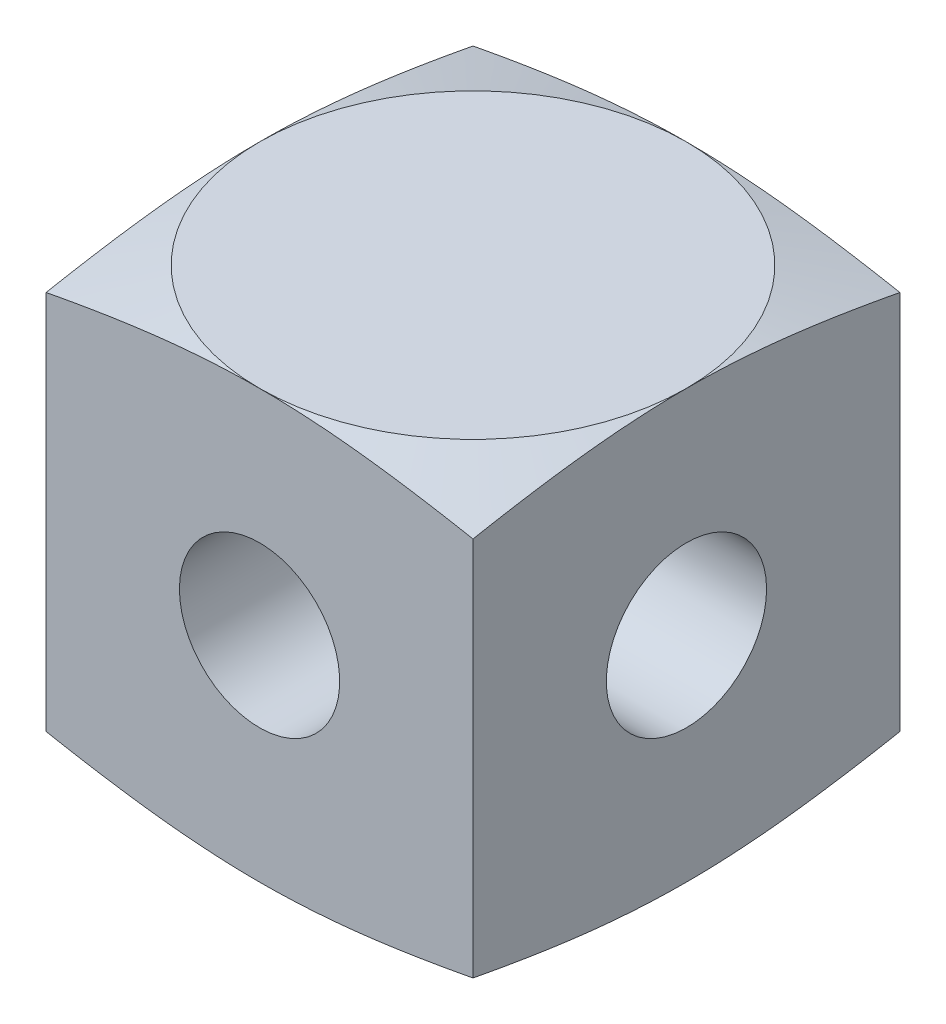
SolidWorks part; units mm, degrees
material "Plain Carbon Steel"
ref_plane "Front Plane" through (0, 0, 0) normal (0, 0, 1) x (1, 0, 0)
ref_plane "Top Plane" through (0, 0, 0) normal (0, 1, 0) x (1, 0, 0)
ref_plane "Right Plane" through (0, 0, 0) normal (1, 0, 0) x (0, 0, -1)
sketch "Sketch1" plane through (0, 0, 0) normal (0, 1, 0) x (1, 0, 0)
  line L1 (6.3437, -6.3437) -> (-6.3437, -6.3437)
  line L2 (6.3437, -6.3437) -> (6.3437, 6.3437)
  line L3 (6.3437, 6.3437) -> (-6.3437, 6.3436)
  line L4 (-6.3437, -6.3437) -> (-6.3437, 6.3436)
  line L5 (6.3437, -6.3437) -> (-6.3437, 6.3436) construction
  line L6 (6.3437, 6.3437) -> (-6.3437, -6.3437) construction
  point P0 (0, 0)
  dimension "D1" = 12.6873
extrude "Boss-Extrude1" add sketch "Sketch1" along normal mid plane 12.7076
sketch "Sketch2" plane through (0, 0, -6.3436) normal (0, 0, -1) x (-1, 0, 0)
  circle A0 centre (0, 0) radius 2.3813
  dimension "D1" = 4.7625
extrude "Cut-Extrude1" cut sketch "Sketch2" against normal through all
sketch "Sketch3" plane through (6.3437, 0, 0) normal (1, 0, 0) x (0, 0, -1)
  circle A0 centre (0, 0) radius 2.3813
  dimension "D1" = 4.7625
extrude "Cut-Extrude2" cut sketch "Sketch3" against normal through all
sketch "Sketch4" plane through (0, 6.3538, 0) normal (0, 1, 0) x (1, 0, 0)
  line L0 (6.3437, -6.3437) -> (6.3437, 6.3437) construction
  circle A0 centre (0, 0) radius 6.3437
  circle A1 centre (0, 0) radius 13.4276
extrude "Cut-Extrude4" cut sketch "Sketch4" against normal blind 12.7076 draft 75
mirror "Mirror1" about plane through (0, 0, 0) normal (0, 1, 0) of "Cut-Extrude4"
